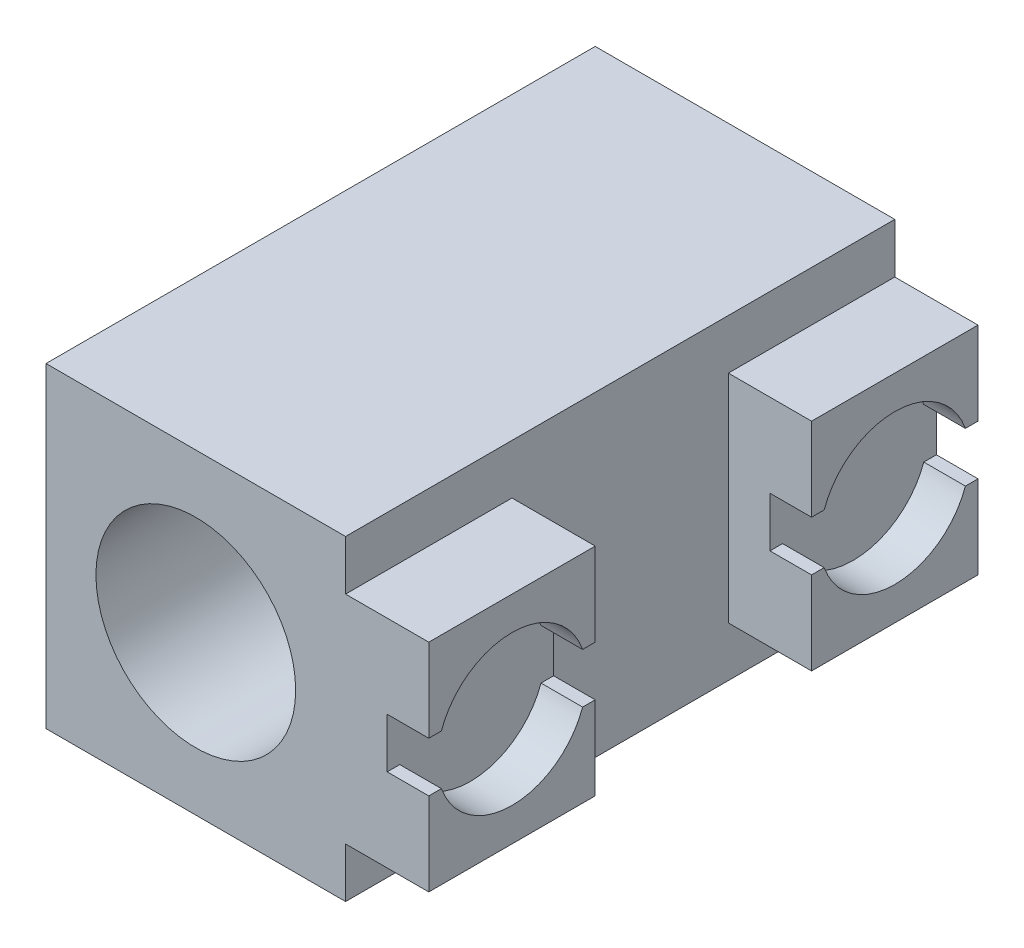
SolidWorks part; units mm, degrees
ref_plane "Front Plane" through (0, 0, 0) normal (0, 0, 1) x (1, 0, 0)
ref_plane "Top Plane" through (0, 0, 0) normal (0, 1, 0) x (1, 0, 0)
ref_plane "Right Plane" through (0, 0, 0) normal (1, 0, 0) x (0, 0, -1)
sketch "Sketch1" plane through (0, 0, 0) normal (0, 0, 1) x (1, 0, 0)
  line L1 (0, 0) -> (36, 0)
  line L2 (0, 0) -> (0, 38)
  line L3 (0, 38) -> (36, 38)
  line L4 (36, 0) -> (36, 38)
  dimension "D1" = 36
  dimension "D2" = 38
extrude "Boss-Extrude1" add sketch "Sketch1" along normal mid plane 66
sketch "Sketch2" plane through (0, 0, 33) normal (0, 0, 1) x (1, 0, 0)
  line L0 (0, 38) -> (0, 0) construction
  line L3 (36, 38) -> (0, 38) construction
  circle A0 centre (18, 19) radius 12
  dimension "D1" = 24
  dimension "D2" = 18
  dimension "D3" = 19
extrude "Cut-Extrude1" cut sketch "Sketch2" against normal through all
sketch "Sketch3" plane through (36, 0, 0) normal (1, 0, 0) x (0, 0, -1)
  line L0 (-33, 32) -> (-13, 32)
  line L1 (-33, 0) -> (-33, 38) construction
  line L2 (-13, 32) -> (-13, 6)
  line L3 (-13, 6) -> (-33, 6)
  line L4 (-33, 6) -> (-33, 32)
  line L5 (33, 32) -> (13, 32)
  line L6 (33, 0) -> (33, 38) construction
  line L7 (13, 32) -> (13, 6)
  line L8 (13, 6) -> (33, 6)
  line L9 (33, 6) -> (33, 32)
  point P10 (17.4962, 5.38)
  point P13 (0, 0)
  dimension "D1" = 6
  dimension "D2" = 6
  dimension "D3" = 20
extrude "Boss-Extrude2" add sketch "Sketch3" along normal blind 10
sketch "Sketch7" plane through (46, 0, 0) normal (1, 0, 0) x (0, 0, -1)
  line L0 (-13, 32) -> (-33, 32) construction
  line L3 (-33, 32) -> (-33, 6) construction
  line L7 (13, 32) -> (13, 6) construction
  circle A0 centre (-23, 19) radius 9
  circle A1 centre (23, 19) radius 9
  point P4 (0, 0)
  dimension "D1" = 18
  dimension "D2" = 13
  dimension "D3" = 10
  dimension "D4" = 10
extrude "Cut-Extrude4" cut sketch "Sketch7" against normal blind 5
sketch "Sketch8" plane through (0, 0, 33) normal (0, 0, 1) x (1, 0, 0)
  line L0 (46, 19) -> (46, 22)
  line L1 (46, 32) -> (46, 6) construction
  line L2 (46, 22) -> (41, 22)
  line L3 (41, 22) -> (41, 16)
  line L4 (41, 16) -> (46, 16)
  line L5 (46, 16) -> (46, 19)
  dimension "D1" = 3
  dimension "D2" = 3
  dimension "D3" = 5
extrude "Cut-Extrude5" cut sketch "Sketch8" against normal through all
